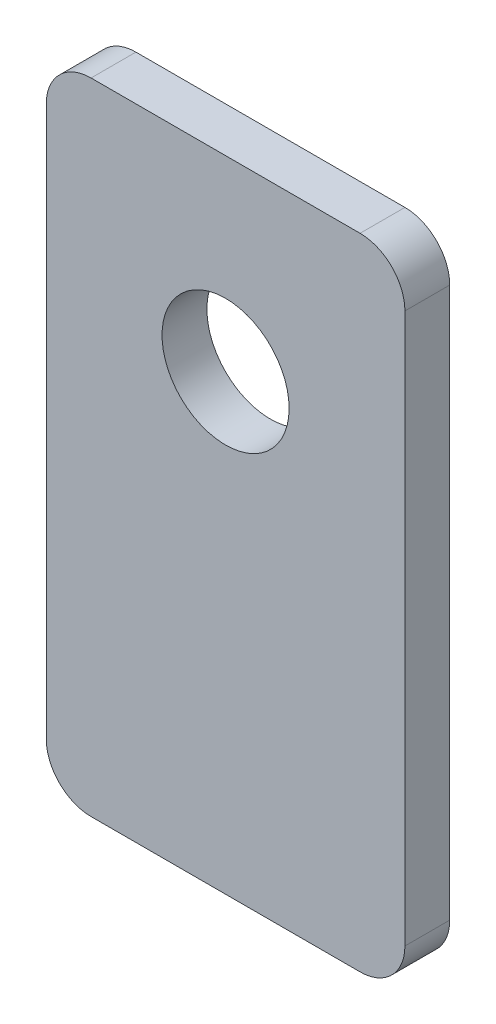
SolidWorks part; units mm, degrees
material "6061 Alloy"
ref_plane "Front Plane" through (0, 0, 0) normal (0, 0, 1) x (1, 0, 0)
ref_plane "Top Plane" through (0, 0, 0) normal (0, 1, 0) x (1, 0, 0)
ref_plane "Right Plane" through (0, 0, 0) normal (1, 0, 0) x (0, 0, -1)
sketch "Sketch1" plane through (0, 0, 0) normal (0, 0, 1) x (1, 0, 0)
  line L1 (-12.7, -22.65) -> (12.7, -22.65)
  line L2 (-12.7, -22.65) -> (-12.7, 22.65)
  line L3 (-12.7, 22.65) -> (12.7, 22.65)
  line L4 (12.7, -22.65) -> (12.7, 22.65)
  line L5 (-12.7, -22.65) -> (12.7, 22.65) construction
  line L6 (-12.7, 22.65) -> (12.7, -22.65) construction
  point P0 (0, 0)
  dimension "D1" = 25.4
  dimension "D2" = 45.3
extrude "Boss-Extrude1" add sketch "Sketch1" along normal blind 3.175
sketch "Sketch2" plane through (0, 0, 3.175) normal (0, 0, 1) x (1, 0, 0)
  line L0 (12.7, -22.65) -> (12.7, 22.65) construction
  line L1 (12.7, 22.65) -> (-12.7, 22.65) construction
  circle A0 centre (0, 9.4) radius 4.5
  dimension "D1" = 9
  dimension "D2" = 12.7
  dimension "D3" = 13.25
extrude "Cut-Extrude1" cut sketch "Sketch2" against normal through all
ref_plane "Plane1" through (0, 0, 3.175) normal (0, 0, 1) x (1, 0, 0)
fillet "Fillet1" radius 3.175 4 edges at (-12.7, 22.65, 1.5875) (-12.7, -22.65, 1.5875) (12.7, -22.65, 1.5875) (12.7, 22.65, 1.5875)
sketch "Sketch3" [suppressed] plane through (0, 0, 3.175) normal (0, 0, 1) x (1, 0, 0)
  line L0 (-9.525, -22.65) -> (9.525, -22.65) construction
  line L1 (-12.7, 19.475) -> (-12.7, -19.475) construction
  point P0 (-6.35, -15.15)
  point P1 (6.35, -15.15)
  dimension "D1" = 7.5
  dimension "D2" = 6.35
  dimension "D3" = 12.7
hole_wizard "M4x0.7 Tapped Hole1" [suppressed] positions "Sketch4" profile "Sketch5" tap size "M4x0.7" standard "ANSI Metric"
sketch "Sketch4" [suppressed] plane through (0, 0, 3.175) normal (0, 0, 1) x (1, 0, 0)
  point P0 (-6.35, -15.15)
  point P3 (6.35, -15.15)
sketch "Sketch5" plane through (-6.35, -15.15, 3.175) normal (1, 0, 0) x (0, -1, 0)
  line L0 (0, 0) -> (0, 3.175)
  line L1 (0, 3.175) -> (1.65, 3.175)
  line L2 (1.65, 3.175) -> (1.65, 0)
  line L5 (1.65, 0) -> (0, 0)
  line L11 (0, -6.35) -> (0, 107.95) construction
  dimension "Thru Tap Drill Dia." = 3.3
  dimension "Thru Tap Drill Depth" = 3.175
